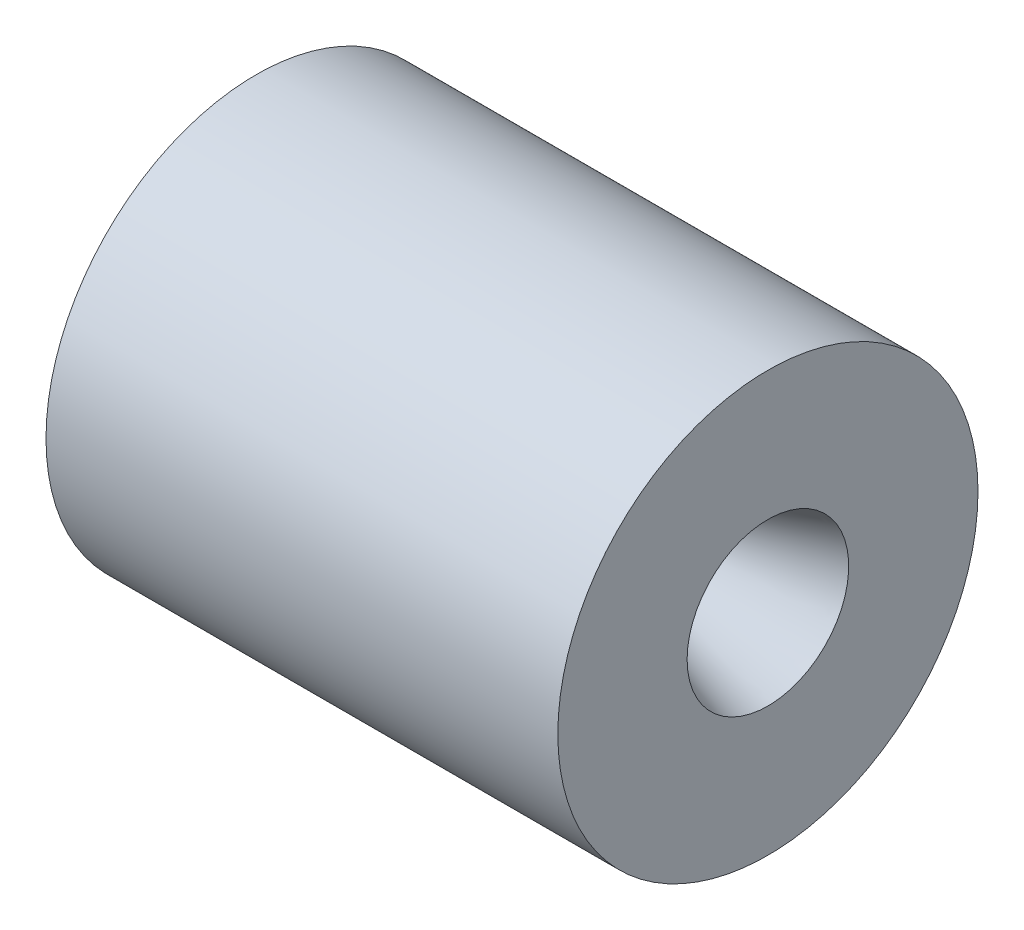
SolidWorks part; units mm, degrees
ref_plane "Front Plane" through (0, 0, 0) normal (0, 0, 1) x (1, 0, 0)
ref_plane "Top Plane" through (0, 0, 0) normal (0, 1, 0) x (1, 0, 0)
ref_plane "Right Plane" through (0, 0, 0) normal (1, 0, 0) x (0, 0, -1)
sketch "Model" plane through (0, 0, 0) normal (0, 0, 1) x (1, 0, 0)
  line L0 (0, 55.1403) -> (23.151, 55.1403)
  line L1 (95.1514, 35.8478) -> (128.5669, 16.5553)
  line L2 (0, 0) -> (185.6492, 0) construction
  line L3 (0, 55.1403) -> (0, 76.2003)
  line L4 (0, 76.2003) -> (185.6492, 76.2003)
  line L5 (185.6492, 76.2003) -> (185.6492, 29.3103)
  arc A0 (95.1514, 35.8478) -> (23.151, 55.1403) centre (23.151, -88.8606) ccw
  arc A1 (128.5669, 16.5553) -> (138.9057, 13.7851) centre (138.9057, 34.4627) ccw
  arc A2 (138.9057, 13.7851) -> (140.6089, 14.0681) centre (138.9057, 19.051) ccw
  spline S0 degree 2 poles (140.6089, 14.0681) (181.4601, 28.0309) (185.6492, 29.3103) knots 0 0 0 1 1 1
  dimension "D1" = 55.1403
  dimension "D2" = 21.06
revolve "Revolve1" add sketch "Model" angle 360 about L2
hole_wizard "#21 (0.159) Diameter Hole1" positions "Sketch2" profile "Sketch3" hole size "#21" standard "ANSI Inch"
sketch "Sketch2" plane through (0, 0, 0) normal (-1, 0, 0) x (0, 0, 1)
  point P0 (69, 0)
  dimension "D1" = 69
sketch "Sketch3" plane through (0, 0, 69) normal (0, 1, 0) x (0, 0, 1)
  line L0 (0, 0) -> (0, 26.2133)
  line L1 (0, 26.2133) -> (2.0193, 25)
  line L2 (2.0193, 25) -> (2.0193, 0)
  line L5 (2.0193, 0) -> (0, 0)
  line L10 (0, 26.2133) -> (-2.0193, 25) construction
  line L11 (0, -6.35) -> (0, 107.95) construction
  dimension "Hole Dia." = 4.0386
  dimension "Hole Depth" = 25
  dimension "Drill Angle" = 118
pattern_circular "CirPattern1" count 12 over 360 about axis through (0, 0, 0) along (1, 0, 0) of "#21 (0.159) Diameter Hole1"
